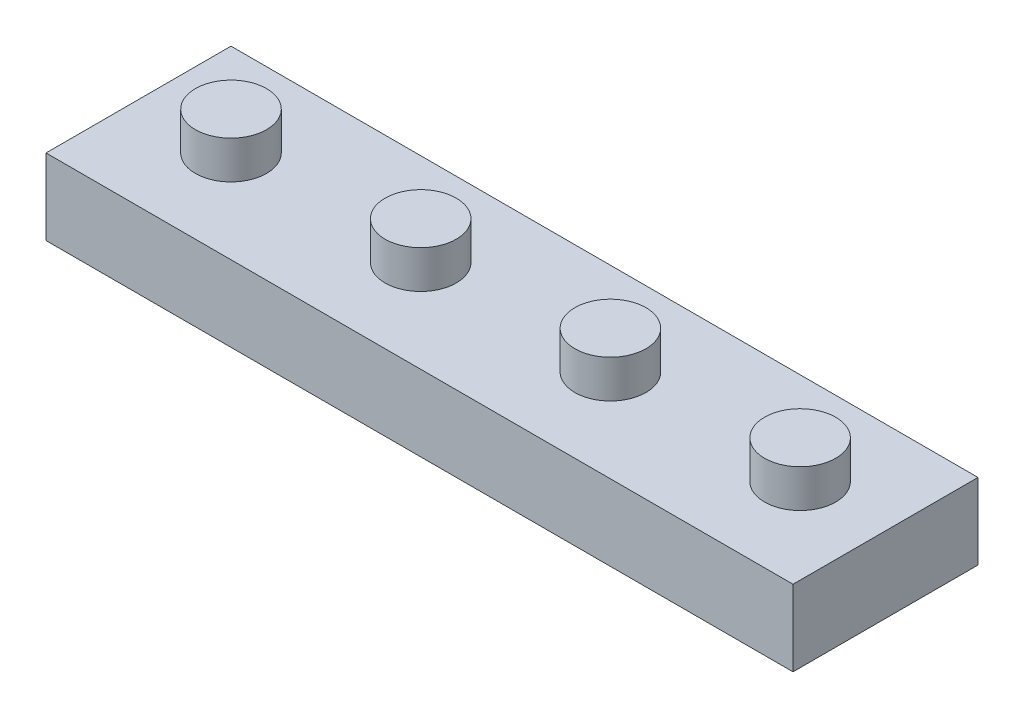
SolidWorks part; units mm, degrees
material "ABS"
ref_plane "Front Plane" through (0, 0, 0) normal (0, 0, 1) x (1, 0, 0)
ref_plane "Top Plane" through (0, 0, 0) normal (0, 1, 0) x (1, 0, 0)
ref_plane "Right Plane" through (0, 0, 0) normal (1, 0, 0) x (0, 0, -1)
sketch "Sketch1" plane through (0, 0, 0) normal (0, 0, 1) x (1, 0, 0)
  line L1 (0, 0) -> (31.5, 0)
  line L2 (0, 0) -> (0, 3.2)
  line L3 (0, 3.2) -> (31.5, 3.2)
  line L4 (31.5, 0) -> (31.5, 3.2)
  line L5 (0, 0) -> (31.5, 3.2) construction
  line L6 (0, 3.2) -> (31.5, 0) construction
  point P4 (15.75, 1.6)
  dimension "D1" = 31.5
  dimension "D2" = 3.2
extrude "Boss-Extrude1" add sketch "Sketch1" against normal blind 7.8
sketch "Sketch2" plane through (0, 3.2, 0) normal (0, 1, 0) x (1, 0, 0)
  line L0 (31.5, 0) -> (0, 0) construction
  circle A0 centre (3.9, 3.9) radius 1.5
  dimension "D1" = 3
  dimension "D2" = 3.9
  dimension "D3" = 3.9
extrude "Boss-Extrude2" add sketch "Sketch2" along normal blind 1.6
pattern_linear "LPattern1" count 2 spacing 8 along (0, 0, 1) count 4 spacing 8 along (1, 0, 0) of "Boss-Extrude2"
shell "Shell1" thickness 1.2
sketch "Sketch3" plane through (0, 2, 0) normal (0, -1, 0) x (1, 0, 0)
  line L0 (0, 0) -> (31.5, 0) construction
  line L1 (0, -7.8) -> (0, 0) construction
  circle A0 centre (7.9, -3.9) radius 1.5
  circle A1 centre (7.9, -3.9) radius 0.6
  dimension "D1" = 3
  dimension "D2" = 1.2
  dimension "D3" = 3.9
  dimension "D4" = 7.9
extrude "Boss-Extrude3" add sketch "Sketch3" along normal offset from surface (1.8 mm away) 0.2 up to face at (15.75, 0, -3.9)
pattern_linear "LPattern2" count 3 spacing 8 along (1, 0, 0) of "Boss-Extrude3"
